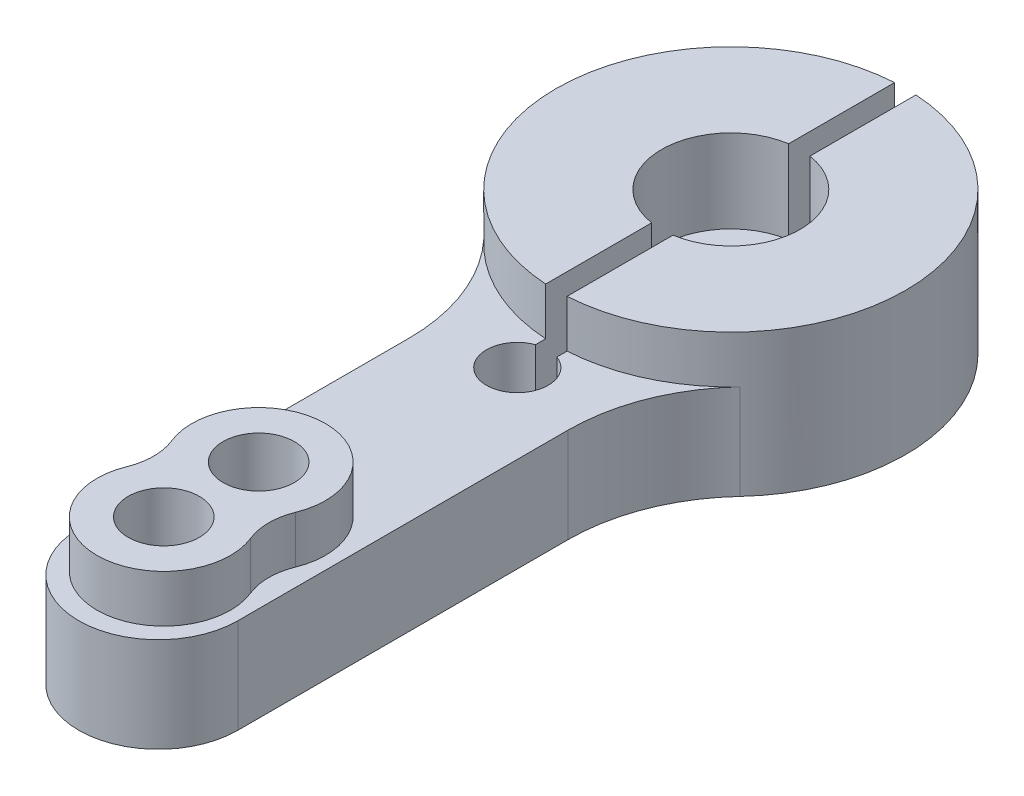
SolidWorks part; units mm, degrees
material "Alloy Steel"
ref_plane "Front Plane" through (0, 0, 0) normal (0, 0, 1) x (1, 0, 0)
ref_plane "Top Plane" through (0, 0, 0) normal (0, 1, 0) x (1, 0, 0)
ref_plane "Right Plane" through (0, 0, 0) normal (1, 0, 0) x (0, 0, -1)
sketch "Sketch1" plane through (0, 0, 0) normal (0, 1, 0) x (1, 0, 0)
  line L0 (-3.3528, -24.13) -> (-3.3528, -6.5587)
  line L1 (3.3528, -24.13) -> (3.3528, -6.5587)
  line L2 (-0.45, -7.7804) -> (-0.45, -1.3257)
  line L3 (0.45, 7.3522) -> (0.45, 1.3257)
  line L4 (-0.45, 1.3257) -> (-0.45, 7.3522)
  line L5 (0.45, -1.3257) -> (0.45, -7.7804)
  arc A0 (3.3528, -6.5587) -> (0.45, 7.3522) centre (0, 0) ccw
  arc A1 (-3.3528, -24.13) -> (3.3528, -24.13) centre (0, -24.13) ccw
  circle A2 centre (0, -23.9) radius 1.5
  circle A3 centre (0, -19.9) radius 1.5
  arc A4 (-0.45, 1.3257) -> (-0.45, -1.3257) centre (0, 0) ccw
  arc A5 (-0.45, -7.7804) -> (0.45, -7.7804) centre (0, -9) ccw
  arc A6 (-0.45, 7.3522) -> (-3.3528, -6.5587) centre (0, 0) ccw
  arc A7 (0.45, -1.3257) -> (0.45, 1.3257) centre (0, 0) ccw
  dimension "D1" = 7.366
  dimension "D2" = 6.7056
  dimension "D3" = 24.13
  dimension "D4" = 3
  dimension "D5" = 3
  dimension "D6" = 2.6
  dimension "D7" = 2.8
  dimension "D8" = 23.9
  dimension "D9" = 19.9
  dimension "D10" = 9
  dimension "D11" = 0.9
  dimension "D12" = 0.45
extrude "Boss-Extrude1" add sketch "Sketch1" against normal blind 4
sketch "Sketch2" plane through (0, 0, 0) normal (0, 1, 0) x (1, 0, 0)
  line L0 (-0.45, 7.3522) -> (-0.45, 1.3257)
  line L1 (0.45, 7.3522) -> (0.45, 1.3257)
  line L2 (-0.45, -1.3257) -> (-0.45, -7.3522)
  line L3 (0.45, -1.3257) -> (0.45, -7.3522)
  arc A0 (-0.45, 7.3522) -> (-0.45, -7.3522) centre (0, 0) ccw
  arc A1 (0.45, -7.3522) -> (0.45, 7.3522) centre (0, 0) ccw
  arc A2 (-0.45, 1.3257) -> (-0.45, -1.3257) centre (0, 0) ccw
  arc A3 (0.45, -1.3257) -> (0.45, 1.3257) centre (0, 0) ccw
  dimension "D1" = 1.4
extrude "Boss-Extrude2" add sketch "Sketch2" along normal blind 2
sketch "Sketch3" plane through (0, 0, 0) normal (0, 1, 0) x (1, 0, 0)
  arc A0 (2.6113, -20.9514) -> (-2.6113, -20.9514) centre (0, -19.9) ccw
  arc A1 (-2.6113, -22.8486) -> (2.6113, -22.8486) centre (0, -23.9) ccw
  arc A2 (2.6113, -20.9514) -> (2.6113, -22.8486) centre (4.9675, -21.9) ccw
  arc A3 (-2.6113, -20.9514) -> (-2.6113, -22.8486) centre (-4.9675, -21.9) cw
  circle A4 centre (0, -19.9) radius 1.5
  circle A5 centre (0, -23.9) radius 1.5
  dimension "D1" = 5.63
  dimension "D2" = 2.54
  dimension "D3" = 3
  dimension "D4" = 3
extrude "Boss-Extrude3" add sketch "Sketch3" along normal blind 2
sketch "Sketch4" plane through (0, 2, 0) normal (0, 1, 0) x (1, 0, 0)
  circle A0 centre (0, 0) radius 2.921
  dimension "D1" = 5.842
extrude "Cut-Extrude1" cut sketch "Sketch4" against normal blind 3.5052
fillet "Fillet1" radius 7.62 2 edges at (-3.3528, -2, 6.5587) (3.3528, -2, 6.5587)
sketch "Sketch5" plane through (0, -4, 0) normal (0, -1, 0) x (1, 0, 0)
  circle A0 centre (0, 0) radius 3.8735
  dimension "D1" = 7.747
extrude "Cut-Extrude2" cut sketch "Sketch5" against normal blind 1.3716
